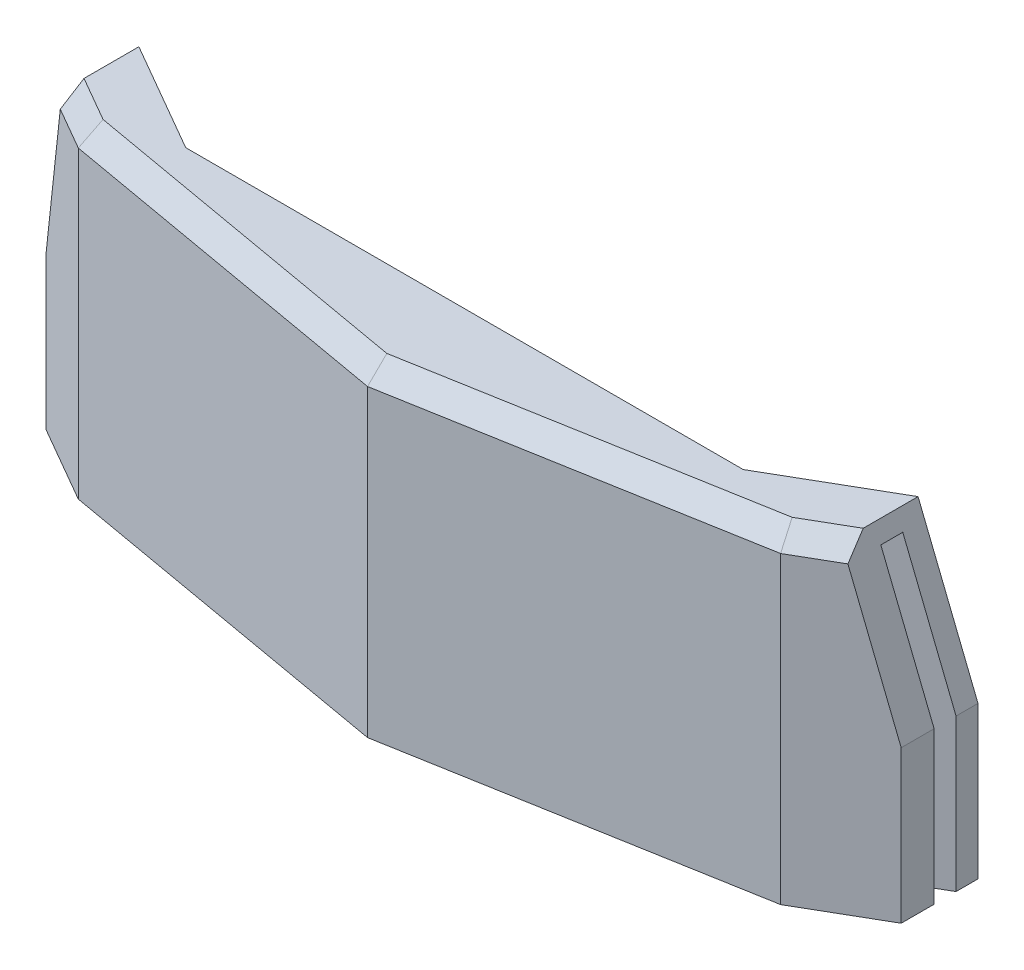
SolidWorks part; units mm, degrees
ref_plane "Front Plane" through (0, 0, 0) normal (0, 0, 1) x (1, 0, 0)
ref_plane "Top Plane" through (0, 0, 0) normal (0, 1, 0) x (1, 0, 0)
ref_plane "Right Plane" through (0, 0, 0) normal (1, 0, 0) x (0, 0, -1)
sketch "Sketch4" plane through (0, 0, 0) normal (0, 1, 0) x (1, 0, 0)
  line L0 (-45, 16.198) -> (-45, 8.1151)
  line L1 (-45, 16.198) -> (-38, 12.1565)
  line L2 (-38, 12.1565) -> (-38, 7.5377)
  line L3 (-38, 7.5377) -> (-35.9121, 6.3323)
  line L4 (-35.9121, 6.3323) -> (0, 0)
  line L5 (0, 0) -> (35.9121, 6.3323)
  line L6 (35.9121, 6.3323) -> (38, 7.5377)
  line L7 (38, 7.5377) -> (38, 12.1565)
  line L8 (38, 12.1565) -> (45, 16.198)
  line L9 (36.954, 3.4697) -> (0, -3.0463)
  line L10 (0, -3.0463) -> (-36.954, 3.4697)
  line L11 (-36.954, 3.4697) -> (-45, 8.1151)
  line L12 (45, 16.198) -> (45, 8.1151)
  line L13 (36.954, 3.4697) -> (45, 8.1151)
  point P14 (0, 0)
  dimension "D1" = 35.9121
  dimension "D2" = 36.954
  dimension "D3" = 38
  dimension "D4" = 45
  dimension "D5" = 3.4697
  dimension "D6" = 6.3323
  dimension "D7" = 7.5377
extrude "Boss-Extrude2" add sketch "Sketch4" along normal blind 34
sketch "Sketch5" plane through (0, 0, 0) normal (0, -1, 0) x (1, 0, 0)
  line L0 (-38, -7.5377) -> (-38, -12.1565) construction
  line L1 (-40, -8.6924) -> (-45, -11.5792)
  line L2 (-45, -16.198) -> (-45, -8.1151) construction
  line L3 (-45, -11.5792) -> (-45, -13.8886)
  line L4 (-45, -13.8886) -> (-40, -11.0018)
  line L6 (-40, -11.0018) -> (-40, -8.6924)
  line L8 (-35.9121, -6.3323) -> (-38, -7.5377) construction
  line L9 (-45, -8.1151) -> (-36.954, -3.4697) construction
  line L10 (-38, -12.1565) -> (-45, -16.198) construction
  line L11 (36.954, -3.4697) -> (45, -8.1151) construction
  line L12 (40, -8.6924) -> (45, -11.5792)
  line L13 (45, -8.1151) -> (45, -16.198) construction
  line L14 (45, -11.5792) -> (45, -13.8886)
  line L15 (45, -13.8886) -> (40, -11.0018)
  line L18 (40, -8.6924) -> (40, -11.0018)
  line L19 (45, -16.198) -> (38, -12.1565) construction
  line L20 (38, -12.1565) -> (38, -7.5377) construction
  dimension "D1" = 2
  dimension "D2" = 3
  dimension "D3" = 2
  dimension "D4" = 3
  dimension "D5" = 2
  dimension "D6" = 2
extrude "Cut-Extrude2" cut sketch "Sketch5" against normal blind 32
sketch "Sketch6" plane through (0, 34, 0) normal (0, 1, 0) x (1, 0, 0)
  line L1 (38, 12.1565) -> (38, 7.5377)
  line L2 (38, 7.5377) -> (35.9121, 6.3323)
  line L3 (35.9121, 6.3323) -> (0, 0)
  line L4 (0, 0) -> (-35.9121, 6.3323)
  line L5 (-35.9121, 6.3323) -> (-38, 7.5377)
  line L6 (-38, 7.5377) -> (-38, 12.1565)
  line L8 (38, 12.1565) -> (29.3397, 7.1565)
  line L9 (-38, 12.1565) -> (-45, 16.198) construction
  line L10 (-38, 12.1565) -> (-29.3397, 7.1565)
  line L11 (-29.3397, 7.1565) -> (29.3397, 7.1565)
  dimension "D1" = 10
  dimension "D2" = 10
extrude "Boss-Extrude3" add sketch "Sketch6" against normal blind 2
chamfer "Chamfer1" distance 2 angle 45 4 edges at (40.977, 34, -5.7924) (-40.977, 34, -5.7924) (-18.477, 34, -0.2117) (18.477, 34, -0.2117)
sketch "Sketch7" plane through (0, 0, 0) normal (0, 0, 1) x (1, 0, 0)
  line L10 (-45, 16) -> (-45, 34)
  line L11 (-45, 32) -> (-45, 0) construction
  line L12 (-45, 34) -> (-41, 34)
  line L13 (-45, 34) -> (-36.2594, 34) construction
  line L14 (-41, 34) -> (-45, 16)
  line L15 (45, 16) -> (41, 34)
  line L16 (45, 32) -> (45, 0) construction
  line L17 (36.2594, 34) -> (45, 34) construction
  line L18 (41, 34) -> (45, 34)
  line L19 (45, 34) -> (45, 16)
  dimension "D1" = 102.529
  dimension "D2" = 102.529
extrude "Cut-Extrude3" cut sketch "Sketch7" against normal up to vertex
